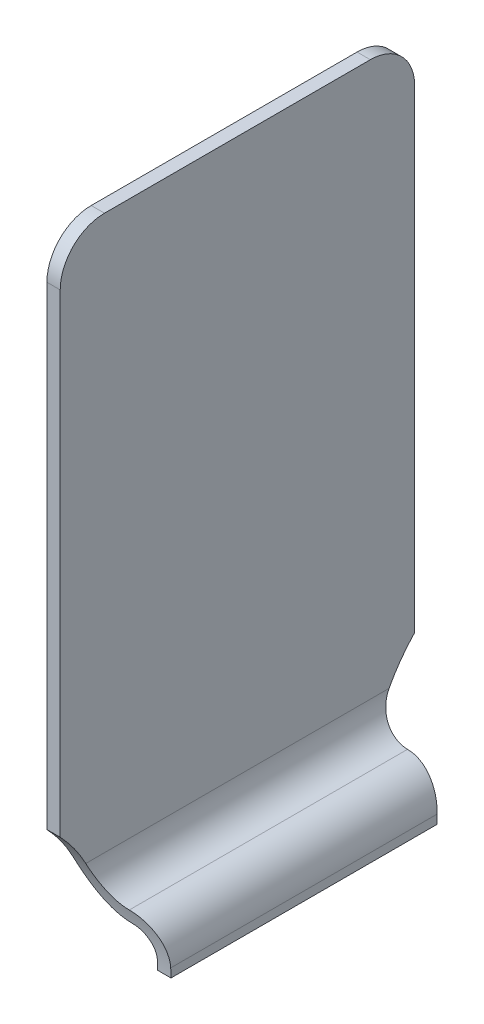
SolidWorks part; units mm, degrees
ref_plane "Front Plane" through (0, 0, 0) normal (0, 0, 1) x (1, 0, 0)
ref_plane "Top Plane" through (0, 0, 0) normal (0, 1, 0) x (1, 0, 0)
ref_plane "Right Plane" through (0, 0, 0) normal (1, 0, 0) x (0, 0, -1)
sketch "Sketch1" plane through (0, 0, 0) normal (0, 0, 1) x (1, 0, 0)
  line L0 (0, 0) -> (0, 5.08)
  line L1 (-38.1, 43.18) -> (-38.1, 360.68)
  arc A0 (0, 5.08) -> (-12.7, 17.78) centre (-12.7, 5.08) ccw
  arc A1 (-12.7, 17.78) -> (-38.1, 43.18) centre (-12.7, 43.18) cw
  point P7 (0, 0)
extrude "Extrude-Thin1" add sketch "Sketch1" along normal mid plane 203.2 thin
fillet "Fillet1" radius 25.4 1 edges at (-34.29, 360.68, 101.6)
fillet "Fillet2" radius 25.4 1 edges at (-34.29, 360.68, -101.6)
sketch3d "3DSketch1"
  point P0 (7.62, 3.3151, 74.6375)
ref_plane "Plane1" through (7.62, 0, 0) normal (1, 0, 0) x (0, 0, -1)
sketch "Sketch3" plane through (7.62, 0, 0) normal (1, 0, 0) x (0, 0, -1)
  line L0 (-101.6, 0) -> (-101.6, 63.5333)
  line L1 (-101.6, 43.18) -> (-101.6, 335.28) construction
  line L2 (-101.6, 0) -> (-76.2, 0)
  line L3 (-101.6, 0) -> (101.6, 0) construction
  line L4 (101.6, 0) -> (76.2, 0)
  line L5 (101.6, 0) -> (101.6, 63.5333)
  line L6 (101.6, 43.18) -> (101.6, 335.28) construction
  arc A0 (-76.2, 0) -> (-101.6, 63.5333) centre (-168.3583, 0) ccw
  arc A1 (76.2, 0) -> (101.6, 63.5333) centre (168.3583, 0) cw
extrude "Cut-Extrude1" cut sketch "Sketch3" against normal blind 54.61 and the other way blind 10.922
